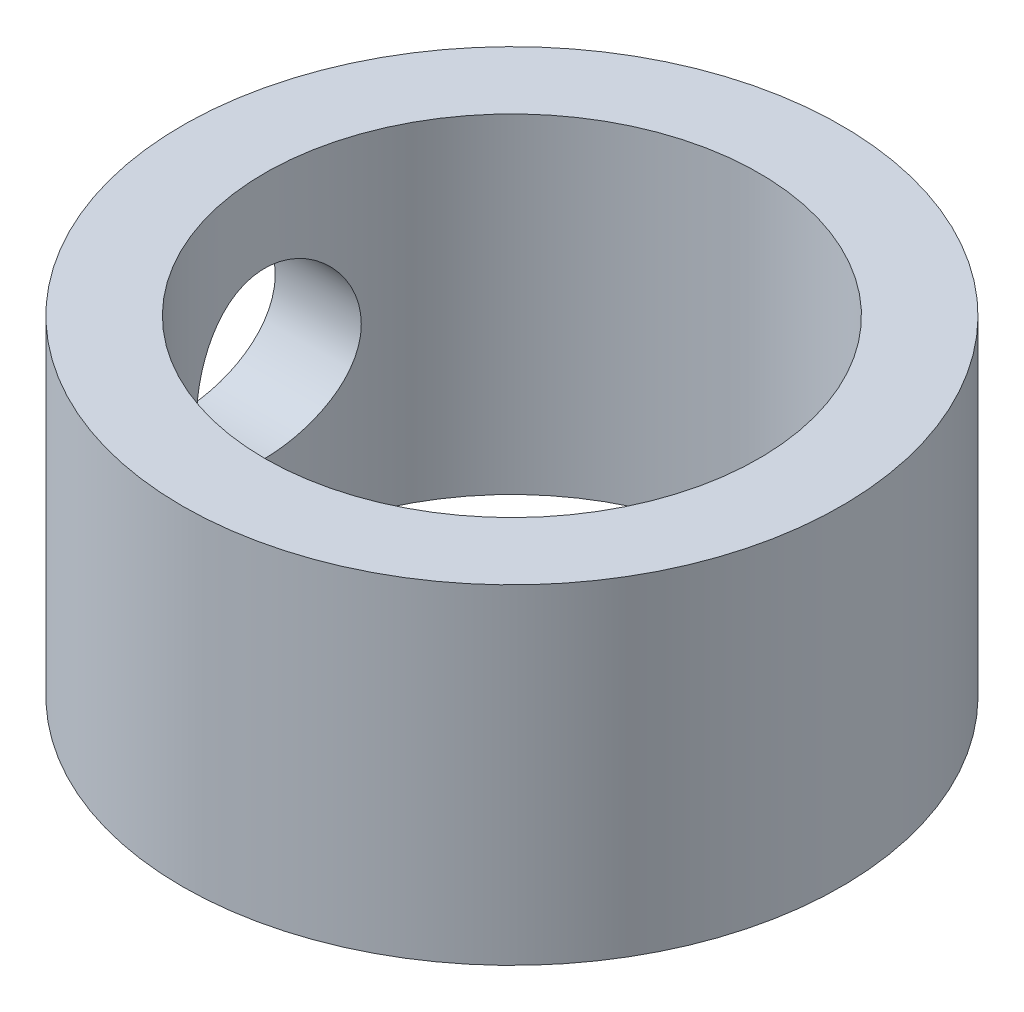
SolidWorks part; units mm, degrees
ref_plane "Front Plane" through (0, 0, 0) normal (0, 0, 1) x (1, 0, 0)
ref_plane "Top Plane" through (0, 0, 0) normal (0, 1, 0) x (1, 0, 0)
ref_plane "Right Plane" through (0, 0, 0) normal (1, 0, 0) x (0, 0, -1)
sketch "Sketch1" plane through (0, 0, 0) normal (0, 1, 0) x (1, 0, 0)
  circle A0 centre (0, 0) radius 3
  circle A1 centre (0, 0) radius 4
  dimension "D1" = 6
  dimension "D2" = 8
extrude "Boss-Extrude1" add sketch "Sketch1" along normal mid plane 4
sketch "Sketch2" plane through (0, 0, 0) normal (1, 0, 0) x (0, 0, -1)
  circle A0 centre (0, 0) radius 1
  dimension "D1" = 2
extrude "Cut-Extrude1" cut sketch "Sketch2" against normal blind 5
